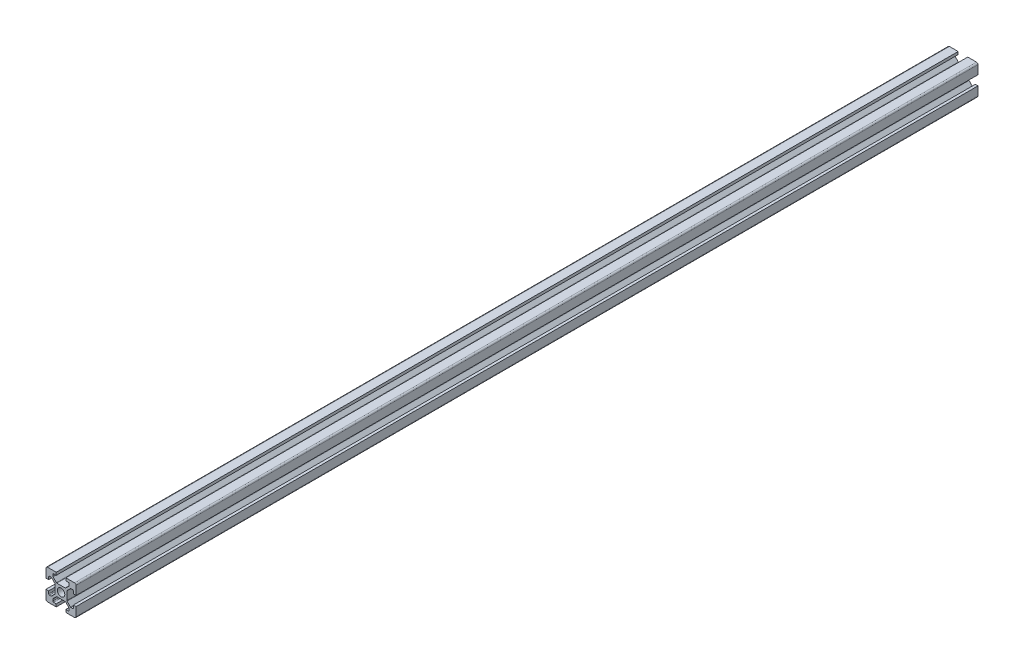
SolidWorks part; units mm, degrees
material "1060 Alloy"
ref_plane "Front Plane" through (0, 0, 0) normal (0, 0, 1) x (1, 0, 0)
ref_plane "Top Plane" through (0, 0, 0) normal (0, 1, 0) x (1, 0, 0)
ref_plane "Right Plane" through (0, 0, 0) normal (1, 0, 0) x (0, 0, -1)
sketch "Sketch1" plane through (0, 0, 0) normal (0, 0, 1) x (1, 0, 0)
  line L0 (20, 0) -> (-8.059, 28.059) construction
  line L1 (0, 0) -> (6.8, 0)
  line L2 (0, 0) -> (0, 6.8)
  line L3 (0, 20) -> (6.8, 20)
  line L4 (20, 0) -> (20, 6.8)
  line L5 (6.8, 20) -> (6.8, 18.2)
  line L6 (20, 20) -> (8.2322, 8.2322) construction
  line L7 (12.95, 6.1) -> (7.05, 6.1)
  line L8 (13.9, 7.05) -> (13.9, 12.95)
  line L9 (12.95, 13.9) -> (7.05, 13.9)
  line L10 (6.1, 7.05) -> (6.1, 12.95)
  line L11 (13.9, 6.1) -> (6.1, 13.9) construction
  line L12 (13.9, 13.9) -> (6.1, 6.1) construction
  line L13 (4.55, 16.4) -> (7.05, 13.9)
  line L14 (13.2, 18.2) -> (13.2, 20)
  line L15 (1.8, 6.8) -> (0, 6.8)
  line L16 (0, 13.2) -> (0, 20)
  line L17 (0, 13.2) -> (1.8, 13.2)
  line L18 (10, 10) -> (10, 13.9) construction
  line L19 (16.4, 4.55) -> (13.9, 7.05)
  line L20 (4.55, 16.4) -> (4.55, 18.2)
  line L21 (4.55, 18.2) -> (6.8, 18.2)
  line L22 (13.2, 18.2) -> (15.45, 18.2)
  line L23 (15.45, 18.2) -> (15.45, 16.4)
  line L24 (15.45, 16.4) -> (12.95, 13.9)
  line L25 (16.4, 4.55) -> (18.2, 4.55)
  line L26 (18.2, 4.55) -> (18.2, 6.8)
  line L27 (20, 6.8) -> (18.2, 6.8)
  line L28 (18.2, 13.2) -> (20, 13.2)
  line L29 (18.2, 13.2) -> (18.2, 15.45)
  line L30 (18.2, 15.45) -> (16.4, 15.45)
  line L31 (16.4, 15.45) -> (13.9, 12.95)
  line L32 (1.8, 4.55) -> (3.6, 4.55)
  line L33 (3.6, 15.45) -> (6.1, 12.95)
  line L34 (3.6, 15.45) -> (1.8, 15.45)
  line L35 (1.8, 15.45) -> (1.8, 13.2)
  line L36 (0, 13.2) -> (1.8, 13.2)
  line L37 (1.8, 6.8) -> (0, 6.8)
  line L38 (3.6, 4.55) -> (6.1, 7.05)
  line L39 (1.8, 6.8) -> (1.8, 4.55)
  line L40 (15.45, 3.6) -> (12.95, 6.1)
  line L41 (4.55, 3.6) -> (7.05, 6.1)
  line L42 (4.55, 1.8) -> (4.55, 3.6)
  line L43 (6.8, 1.8) -> (4.55, 1.8)
  line L44 (6.8, 1.8) -> (6.8, 0)
  line L45 (15.45, 3.6) -> (15.45, 1.8)
  line L46 (15.45, 1.8) -> (13.2, 1.8)
  line L47 (13.2, 0) -> (13.2, 1.8)
  line L48 (13.2, 20) -> (20, 20)
  line L49 (20, 13.2) -> (20, 20)
  line L50 (13.2, 0) -> (20, 0)
  line L51 (6.1, 6.1) -> (-5.5045, -5.5045) construction
  circle A0 centre (10, 10) radius 2.5
  point P25 (10, 16.4)
  point P39 (13.2, 19.1)
  point P46 (0.9, 6.8)
  dimension "D3" = 5
  dimension "D2" = 20
  dimension "D4" = 7.8
  dimension "D5" = 7.8
  dimension "D6" = 6.8
  dimension "D7" = 6.8
  dimension "D8" = 1.8
  dimension "D9" = 10.9
  dimension "D10" = 1.8
  dimension "D11" = 10.9
  dimension "D12" = 20
extrude "Boss-Extrude1" add sketch "Sketch1" along normal blind 600 contours L47 L50 L4 L27 L26 L25 L19 L8 L31 L30 L29 L28 L49 L48 L14 L22 L23 L24 L9 L13 L20 L21 L5 L3 L16 L17 L35 L34 L33 L10 L38 L32 L39 L15 L2 L1 L44 L43 L42 L41 L7 L40 L45 L46 A0
fillet "Fillet1" radius 1 4 edges at (20, 20, 300) (20, 0, 300) (0, 0, 300) (0, 20, 300)
fillet "Fillet2" radius 0.5 6 edges at (4.55, 18.2, 300) (4.55, 16.4, 300) (7.05, 13.9, 300) (15.45, 18.2, 300) (15.45, 16.4, 300) (12.95, 13.9, 300)
fillet "Fillet3" radius 0.5 6 edges at (18.2, 15.45, 300) (16.4, 15.45, 300) (13.9, 12.95, 300) (18.2, 4.55, 300) (13.9, 7.05, 300) (16.4, 4.55, 300)
fillet "Fillet4" radius 0.5 6 edges at (1.8, 15.45, 300) (3.6, 15.45, 300) (6.1, 12.95, 300) (3.6, 4.55, 300) (1.8, 4.55, 300) (6.1, 7.05, 300)
fillet "Fillet5" radius 0.5 6 edges at (7.05, 6.1, 300) (4.55, 3.6, 300) (4.55, 1.8, 300) (15.45, 1.8, 300) (15.45, 3.6, 300) (12.95, 6.1, 300)
sketch "Sketch2" plane through (0, 24, 0) normal (0, 1, 0) x (1, 0, 0)
  circle A0 centre (10, -10) radius 2.5
  circle A1 centre (10, -390) radius 2.5
extrude "Cut-Extrude1" cut sketch "Sketch2" against normal up to surface (17.9 mm away) up to face at (10, 6.1, 300)
